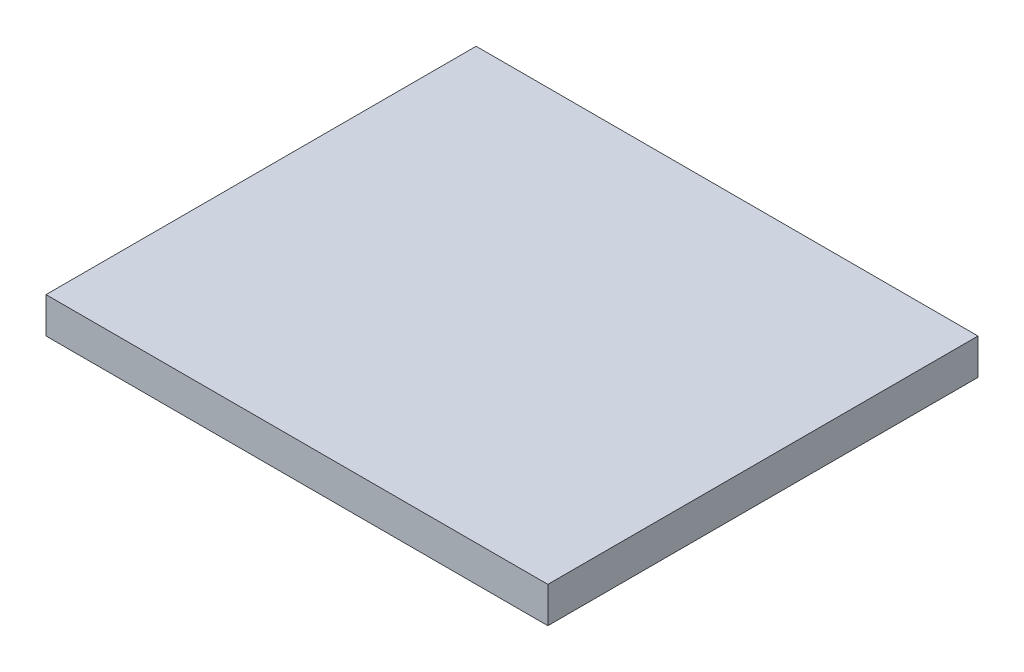
SolidWorks part; units mm, degrees
material "Epoxy, Unfilled"
ref_plane "Front Plane" through (0, 0, 0) normal (0, 0, 1) x (1, 0, 0)
ref_plane "Top Plane" through (0, 0, 0) normal (0, 1, 0) x (1, 0, 0)
ref_plane "Right Plane" through (0, 0, 0) normal (1, 0, 0) x (0, 0, -1)
sketch "Sketch1" plane through (0, 0, 0) normal (0, 1, 0) x (1, 0, 0)
  line L1 (-1.75, -1.5) -> (1.75, -1.5)
  line L2 (-1.75, -1.5) -> (-1.75, 1.5)
  line L3 (-1.75, 1.5) -> (1.75, 1.5)
  line L4 (1.75, -1.5) -> (1.75, 1.5)
  line L5 (-1.75, -1.5) -> (1.75, 1.5) construction
  line L6 (-1.75, 1.5) -> (1.75, -1.5) construction
  point P0 (0, 0)
  dimension "D1" = 3
  dimension "D2" = 3.5
extrude "Boss-Extrude1" add sketch "Sketch1" along normal mid plane 0.25
